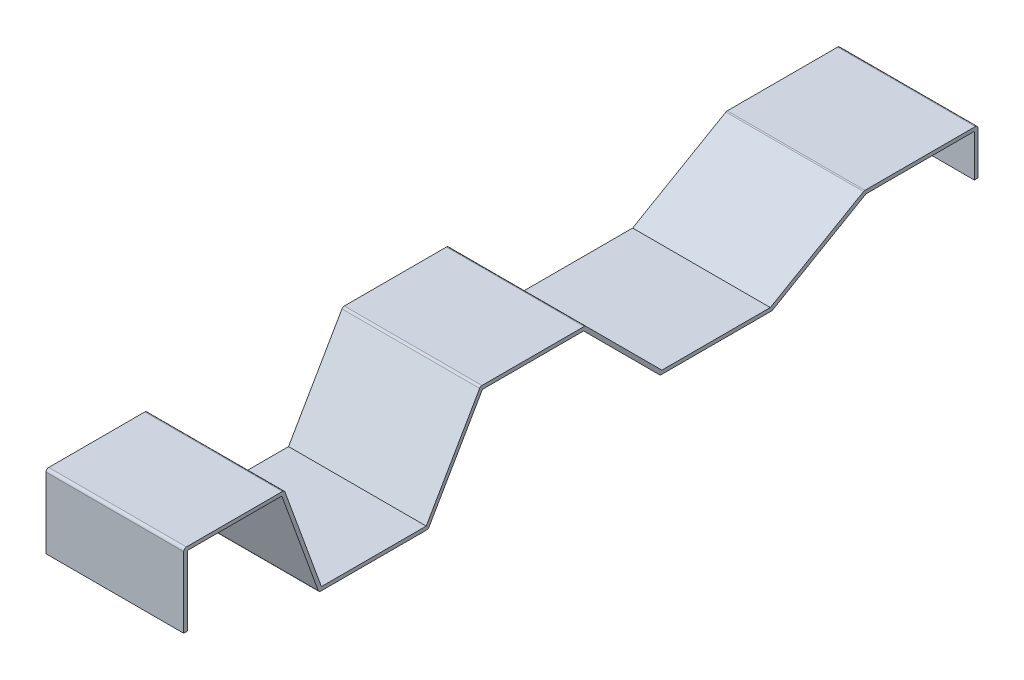
SolidWorks part; units mm, degrees
ref_plane "Front Plane" through (0, 0, 0) normal (0, 0, 1) x (1, 0, 0)
ref_plane "Top Plane" through (0, 0, 0) normal (0, 1, 0) x (1, 0, 0)
ref_plane "Right Plane" through (0, 0, 0) normal (1, 0, 0) x (0, 0, -1)
sketch "Sketch1" plane through (0, 0, 0) normal (1, 0, 0) x (0, 0, -1)
  line L0 (410.976, -727.738) -> (410.976, -702.338)
  line L1 (410.976, -702.338) -> (347.984, -702.338)
  line L2 (347.984, -702.338) -> (296.0225, -732.338)
  line L3 (296.0225, -732.338) -> (236.0225, -732.338)
  line L4 (236.0225, -732.338) -> (193.596, -689.9116)
  line L5 (193.596, -689.9116) -> (135.596, -689.9116)
  line L6 (135.596, -689.9116) -> (105.596, -741.8731)
  line L7 (105.596, -741.8731) -> (47.596, -741.8731)
  line L8 (47.596, -741.8731) -> (27.0748, -685.4916)
  line L9 (27.0748, -685.4916) -> (-28.6352, -685.4916)
  line L10 (-28.6352, -685.4916) -> (-28.6352, -726.1316)
  line L11 (410.976, -727.738) -> (408.976, -727.738)
  line L12 (408.976, -727.738) -> (408.976, -704.338)
  line L13 (408.976, -704.338) -> (348.976, -704.338)
  line L14 (348.976, -704.338) -> (297.0144, -734.338)
  line L15 (297.0144, -734.338) -> (235.122, -734.338)
  line L16 (235.122, -734.338) -> (192.6956, -691.9116)
  line L17 (192.6956, -691.9116) -> (136.6956, -691.9116)
  line L18 (136.6956, -691.9116) -> (106.6956, -743.8731)
  line L19 (106.6956, -743.8731) -> (46.1956, -743.8731)
  line L20 (46.1956, -743.8731) -> (25.6744, -687.4916)
  line L21 (25.6744, -687.4916) -> (-26.6352, -687.4916)
  line L22 (-26.6352, -687.4916) -> (-26.6352, -726.1316)
  line L23 (-26.6352, -726.1316) -> (-28.6352, -726.1316)
  dimension "D2" = 60
  dimension "D3" = 60
  dimension "D4" = 60
  dimension "D5" = 58
  dimension "D6" = 120
  dimension "D7" = 60
  dimension "D8" = 60.5
  dimension "D9" = 135
  dimension "D10" = 58
  dimension "D11" = 25.4
  dimension "D12" = 110
  dimension "D13" = 60
  dimension "D14" = 55.71
  dimension "D15" = 40.64
  dimension "D16" = 2
  dimension "D17" = 2
  dimension "D18" = 2
  dimension "D19" = 150
  dimension "D20" = 56
  dimension "D21" = 2
  dimension "D22" = 0
  dimension "D23" = 2
  dimension "D24" = 60
  dimension "D25" = 2
  dimension "D26" = 0
  dimension "D27" = 2
  dimension "D29" = 2
extrude "Boss-Extrude1" add sketch "Sketch1" along normal blind 76.2
fillet "Fillet1" radius 1.5 6 edges at (38.1, -702.338, -410.976) (38.1, -702.338, -347.984) (38.1, -689.9116, -193.596) (38.1, -689.9116, -135.596) (38.1, -685.4916, -27.0748) (38.1, -685.4916, 28.6352)
fillet "Fillet2" radius 1.5 4 edges at (38.1, -743.8731, -46.1956) (38.1, -743.8731, -106.6956) (38.1, -734.338, -235.122) (38.1, -734.338, -297.0144)
fillet "Fillet3" radius 0.5 6 edges at (38.1, -704.338, -408.976) (38.1, -704.338, -348.976) (38.1, -691.9116, -192.6956) (38.1, -691.9116, -136.6956) (38.1, -687.4916, -25.6744) (38.1, -687.4916, 26.6352)
